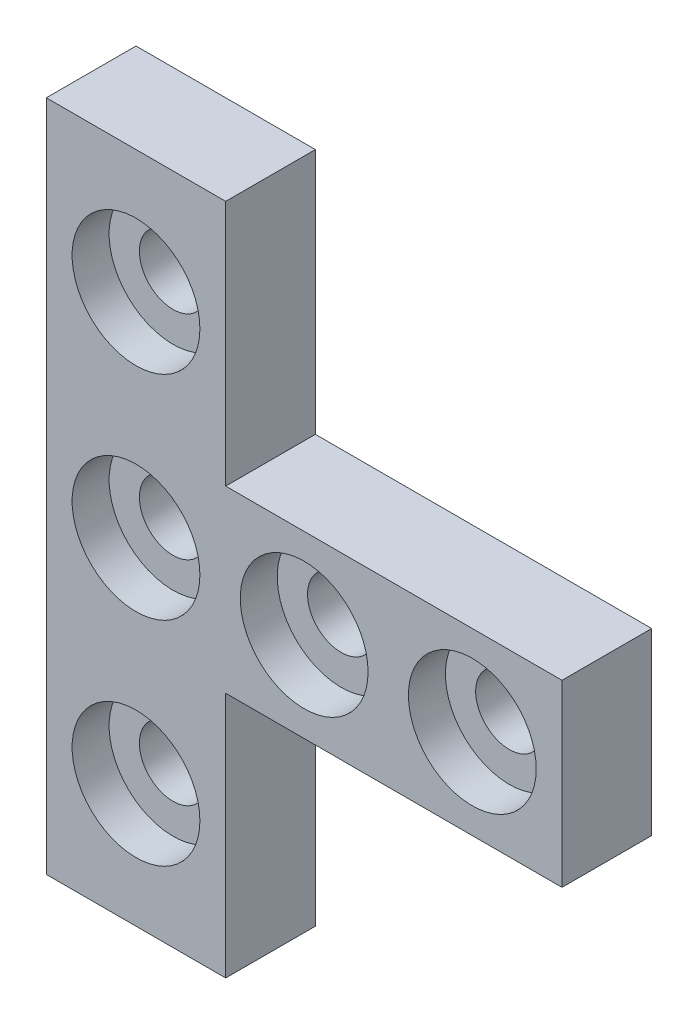
SolidWorks part; units mm, degrees
ref_plane "Alzado" through (0, 0, 0) normal (0, 0, 1) x (1, 0, 0)
ref_plane "Planta" through (0, 0, 0) normal (0, 1, 0) x (1, 0, 0)
ref_plane "Vista lateral" through (0, 0, 0) normal (1, 0, 0) x (0, 0, -1)
sketch "Croquis2" plane through (0, 0, 0) normal (0, 0, 1) x (1, 0, 0)
  line L1 (43.9972, -189.7054) -> (43.9972, -185.7054) construction
  line L2 (38.4972, -99.7054) -> (38.4972, -279.7054) construction
  line L4 (55.9972, -189.7054) -> (55.9972, -185.7054) construction
  line L7 (46.4972, -264.7054) -> (46.4972, -114.7054) construction
  line L21 (38.4972, -264.7054) -> (38.4972, -114.7054) construction
  line L22 (38.4972, -99.7054) -> (38.4972, -279.7054) construction
  line L23 (38.4972, -99.7054) -> (38.4972, -114.7054) construction
  line L24 (38.4972, -114.7054) -> (-55.1416, -114.7054) construction
  line L25 (-55.1416, -264.7054) -> (38.4972, -264.7054) construction
  line L26 (46.4972, -204.7054) -> (46.4972, -193.7054)
  line L27 (46.4972, -185.7054) -> (46.4972, -174.7054)
  line L28 (38.4972, -114.7054) -> (42.4972, -114.7054) construction
  line L29 (57.4972, -114.7054) -> (73.4972, -114.7054) construction
  line L30 (38.4972, -189.7054) -> (222.4972, -189.7054) construction
  line L31 (222.4972, -279.7054) -> (222.4972, -99.7054) construction
  line L35 (42.4972, -204.7054) -> (42.4972, -174.7054) construction
  line L36 (46.4972, -189.7054) -> (38.4972, -189.7054)
  line L37 (46.4972, -189.7054) -> (46.4972, -174.7054) construction
  line L38 (46.4972, -174.7054) -> (38.4972, -174.7054)
  line L39 (38.4972, -189.7054) -> (38.4972, -174.7054)
  line L40 (46.4972, -189.7054) -> (38.4972, -189.7054)
  line L41 (46.4972, -189.7054) -> (46.4972, -204.7054) construction
  line L42 (46.4972, -204.7054) -> (38.4972, -204.7054)
  line L43 (38.4972, -189.7054) -> (38.4972, -204.7054)
  line L44 (46.4972, -193.7054) -> (61.4972, -193.7054)
  line L45 (46.4972, -193.7054) -> (46.4972, -185.7054)
  line L46 (46.4972, -185.7054) -> (61.4972, -185.7054)
  line L47 (61.4972, -193.7054) -> (61.4972, -185.7054)
  line L48 (46.4972, -193.7054) -> (38.4972, -193.7054) construction
  line L49 (46.4972, -185.7054) -> (38.4972, -185.7054) construction
  line L50 (38.4972, -204.7054) -> (46.4972, -193.7054) construction
  line L51 (38.4972, -193.7054) -> (46.4972, -204.7054) construction
  line L52 (46.4972, -185.7054) -> (38.4972, -174.7054) construction
  line L53 (46.4972, -174.7054) -> (38.4972, -185.7054) construction
  circle A0 centre (57.4972, -189.7054) radius 1.5
  circle A2 centre (42.4972, -199.2054) radius 1.5
  circle A5 centre (42.4972, -180.2054) radius 1.5
  circle A6 centre (42.4972, -189.7054) radius 1.5
  circle A7 centre (49.9972, -189.7054) radius 1.5
  dimension "D6" = 3
  dimension "D7" = 3
  dimension "D8" = 3
  dimension "D10" = 3
  dimension "D11" = 3
  dimension "D1" = 8
  dimension "D2" = 15
  dimension "D3" = 15
  dimension "D4" = 8
  dimension "D5" = 15
  dimension "D9" = 4
  dimension "D12" = 6
extrude "Saliente-Extruir1" add sketch "Croquis2" along normal blind 4
sketch "Croquis3" plane through (0, 0, 4) normal (0, 0, 1) x (1, 0, 0)
  circle A0 centre (42.4972, -199.2054) radius 2.85
  circle A2 centre (42.4972, -189.7054) radius 2.85
  circle A3 centre (42.4972, -180.2054) radius 2.85
  circle A4 centre (49.9972, -189.7054) radius 2.85
  circle A5 centre (57.4972, -189.7054) radius 2.85
  dimension "D1" = 5.7
  dimension "D2" = 5.7
extrude "Cortar-Extruir1" cut sketch "Croquis3" against normal blind 1.65
